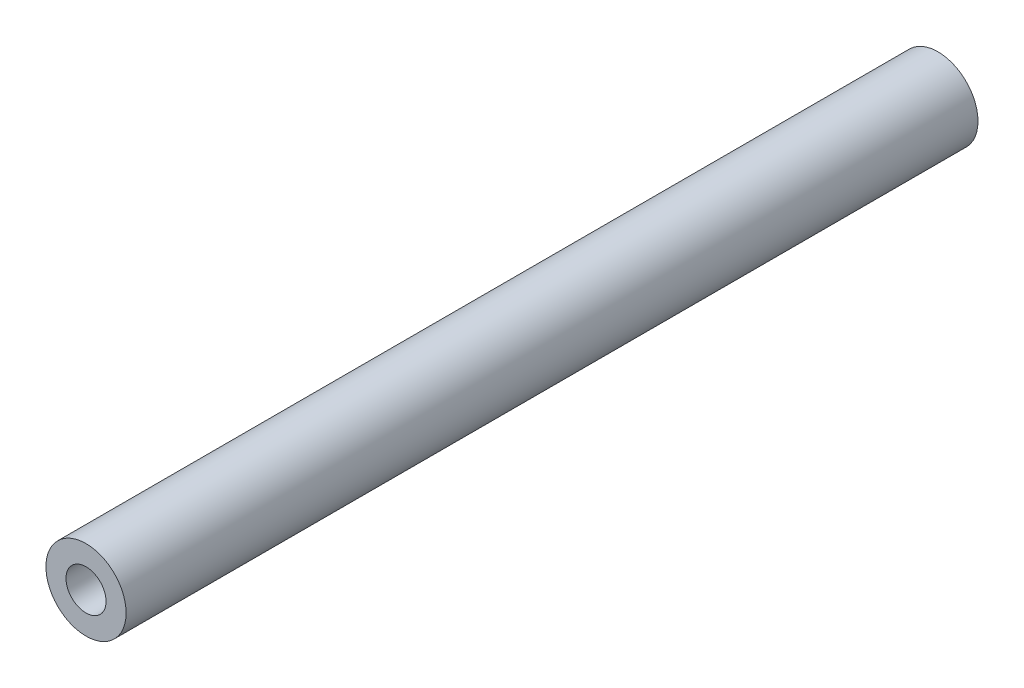
SolidWorks part; units mm, degrees
ref_plane "Front Plane" through (0, 0, 0) normal (0, 0, 1) x (1, 0, 0)
ref_plane "Top Plane" through (0, 0, 0) normal (0, 1, 0) x (1, 0, 0)
ref_plane "Right Plane" through (0, 0, 0) normal (1, 0, 0) x (0, 0, -1)
sketch "Sketch2" plane through (0, 0, 0) normal (0, 0, 1) x (1, 0, 0)
  circle A0 centre (0, 0) radius 101.6
  circle A1 centre (0, 0) radius 50.8
  dimension "D1" = 101.6
  dimension "D2" = 203.2
extrude "Boss-Extrude1" add sketch "Sketch2" along normal mid plane 2159
